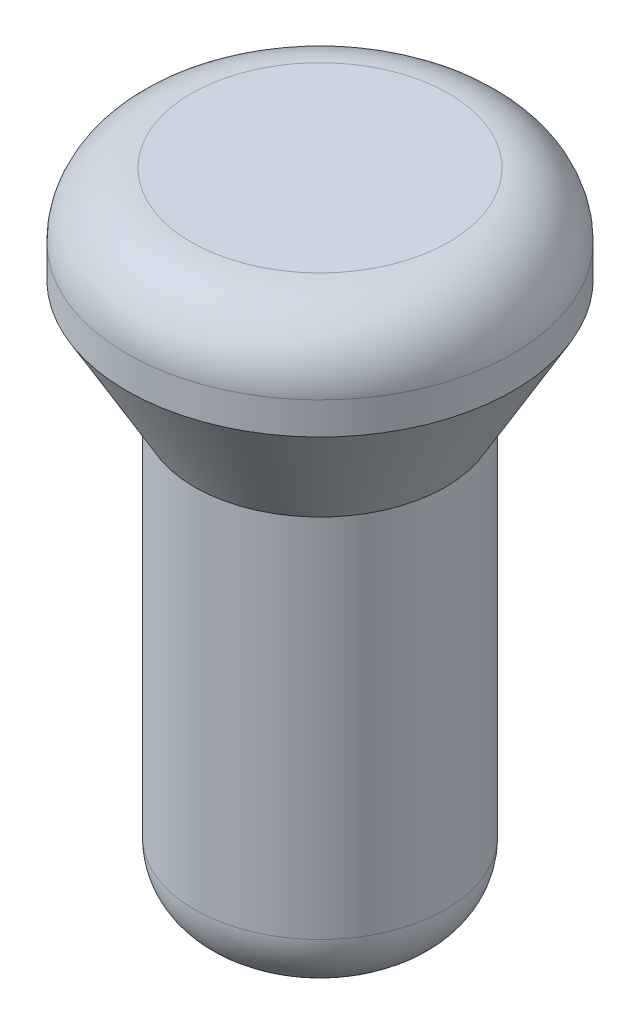
SolidWorks part; units mm, degrees
ref_plane "Front Plane" through (0, 0, 0) normal (0, 0, 1) x (1, 0, 0)
ref_plane "Top Plane" through (0, 0, 0) normal (0, 1, 0) x (1, 0, 0)
ref_plane "Right Plane" through (0, 0, 0) normal (1, 0, 0) x (0, 0, -1)
sketch "Sketch1" plane through (0, 0, 0) normal (1, 0, 0) x (0, 0, -1)
  line L0 (0, 0) -> (0, 14.0697) construction
  line L1 (0, 55) -> (0, -55) construction
  line L2 (0, -4.5) -> (-0.95, -4.5)
  line L3 (-1.95, -3.5) -> (-1.95, 2.1813)
  line L4 (-1.95, 2.1813) -> (-3, 4)
  line L5 (-3, 4) -> (-3, 4.5)
  line L6 (-2, 5.5) -> (0, 5.5)
  line L7 (0, 5.5) -> (0, -4.5)
  line L8 (55, 0) -> (-55, 0) construction
  arc A0 (-3, 4.5) -> (-2, 5.5) centre (-2, 4.5) cw
  arc A1 (-0.95, -4.5) -> (-1.95, -3.5) centre (-0.95, -3.5) cw
  point P19 (-3, 5.5)
  point P22 (-1.95, -4.5)
  dimension "D6" = 1
  dimension "D1" = 1.95
  dimension "D2" = 4
  dimension "D3" = 1.5
  dimension "D4" = 3
  dimension "D5" = 4.5
  dimension "D7" = 30
revolve "Revolve1" add sketch "Sketch1" angle 360 about L0
